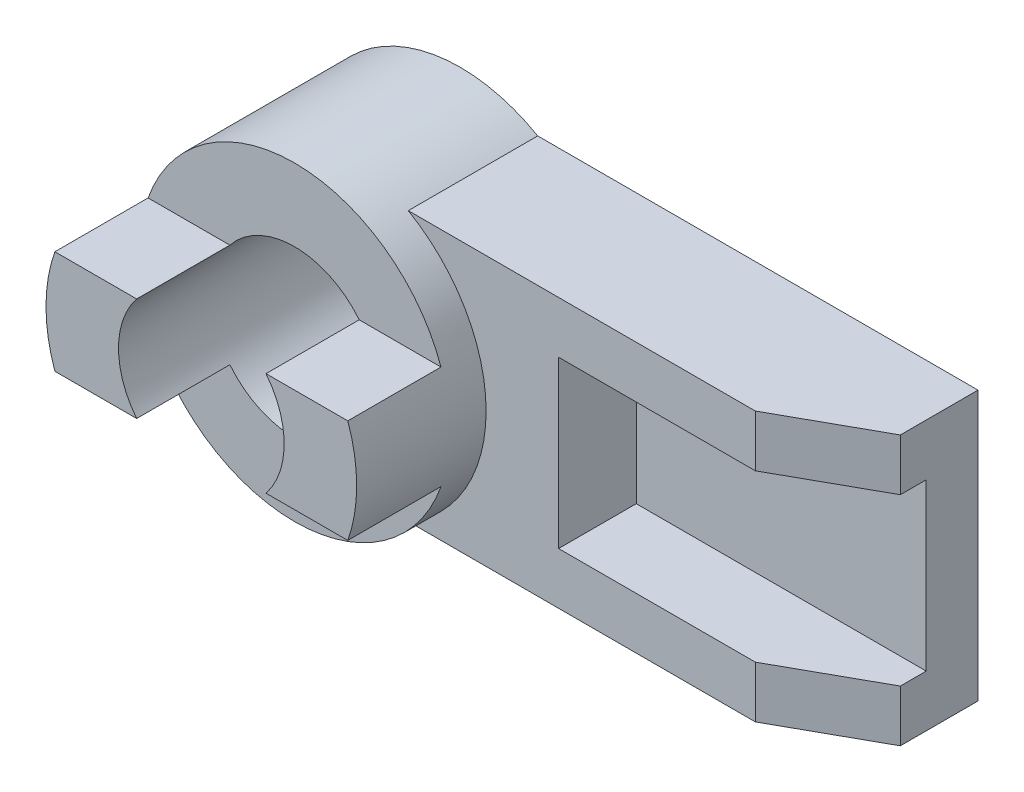
SolidWorks part; units mm, degrees
material "Chrome Stainless Steel"
ref_plane "Front Plane" through (0, 0, 0) normal (0, 0, 1) x (1, 0, 0)
ref_plane "Top Plane" through (0, 0, 0) normal (0, 1, 0) x (1, 0, 0)
ref_plane "Right Plane" through (0, 0, 0) normal (1, 0, 0) x (0, 0, -1)
sketch "Sketch1" plane through (0, 0, 0) normal (0, 0, 1) x (1, 0, 0)
  line L1 (0, 0) -> (100, 0)
  line L2 (0, 0) -> (0, 52)
  line L3 (0, 52) -> (100, 52)
  line L4 (100, 0) -> (100, 52)
  dimension "D1" = 52
  dimension "D2" = 100
extrude "Boss-Extrude1" add sketch "Sketch1" along normal blind 25
sketch "Sketch2" plane through (0, 0, 0) normal (0, 0, -1) x (-1, 0, 0)
  line L0 (0, 52) -> (0, 0) construction
  circle A0 centre (0, 26) radius 30
  dimension "D1" = 60
extrude "Boss-Extrude2" add sketch "Sketch2" against normal blind 50
sketch "Sketch3" plane through (0, 52, 0) normal (0, 1, 0) x (1, 0, 0)
  line L0 (100, -25) -> (100, -15)
  line L1 (100, -25) -> (100, 0) construction
  line L2 (100, -15) -> (82, -25)
  line L3 (100, -25) -> (14.9666, -25) construction
  line L4 (82, -25) -> (100, -25)
  dimension "D1" = 10
  dimension "D2" = 18
extrude "Cut-Extrude1" cut sketch "Sketch3" against normal up to next
sketch "Sketch4" plane through (0, 0, 25) normal (0, 0, 1) x (1, 0, 0)
  line L0 (82, 26) -> (37.9627, 26) construction
  line L1 (82, 0) -> (82, 52) construction
  line L2 (44, 10) -> (44, 42)
  line L3 (44, 42) -> (100, 42)
  line L4 (100, 0) -> (100, 52) construction
  line L5 (100, 42) -> (100, 10)
  line L6 (100, 26) -> (44, 26)
  line L7 (100, 52) -> (82, 52) construction
  line L8 (44, 10) -> (100, 10)
  dimension "D1" = 56
  dimension "D2" = 10
extrude "Cut-Extrude2" cut sketch "Sketch4" against normal blind 15 contours L8 L5 L3 L2
sketch "Sketch5" plane through (0, 0, 50) normal (0, 0, 1) x (1, 0, 0)
  line L1 (-36.9258, 36) -> (36.9258, 36)
  line L2 (-36.9258, 36) -> (-36.9258, 16)
  line L3 (-36.9258, 16) -> (36.9258, 16)
  line L4 (36.9258, 36) -> (36.9258, 16)
  line L5 (-36.9258, 36) -> (36.9258, 16) construction
  line L6 (-36.9258, 16) -> (36.9258, 36) construction
  point P0 (0, 26)
  dimension "D1" = 20
extrude "Cut-Extrude3" cut sketch "Sketch5" against normal blind 18 flip side to cut
sketch "Sketch6" plane through (0, 0, 50) normal (0, 0, 1) x (1, 0, 0)
  circle A0 centre (0, 26) radius 16
  dimension "D1" = 32
extrude "Cut-Extrude4" cut sketch "Sketch6" against normal up to next
